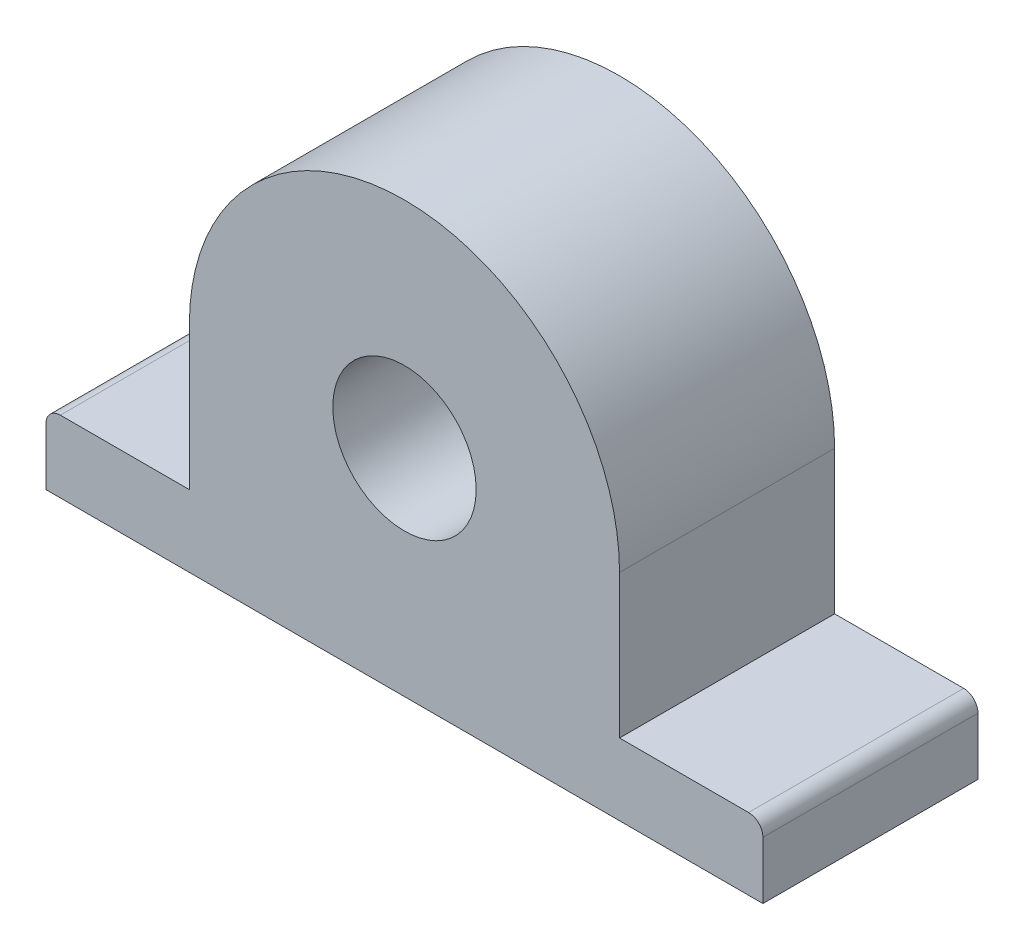
SolidWorks part; units mm, degrees
ref_plane "前视基准面" through (0, 0, 0) normal (0, 0, 1) x (1, 0, 0)
ref_plane "上视基准面" through (0, 0, 0) normal (0, 1, 0) x (1, 0, 0)
ref_plane "右视基准面" through (0, 0, 0) normal (1, 0, 0) x (0, 0, -1)
other "Configuration Table"
sketch "草图1" plane through (0, 0, 0) normal (0, 0, 1) x (1, 0, 0)
  line L0 (15, 2.5) -> (25, 2.5)
  line L1 (-25, 2.5) -> (-15, 2.5)
  line L2 (-25, 2.5) -> (-25, -2.5)
  line L3 (-25, -2.5) -> (25, -2.5)
  line L4 (25, 2.5) -> (25, -2.5)
  line L5 (-25, 2.5) -> (25, -2.5) construction
  line L6 (-25, -2.5) -> (25, 2.5) construction
  line L8 (-15, 12.5) -> (-15, 2.5)
  line L10 (15, 12.5) -> (15, 2.5)
  line L11 (-15, 12.5) -> (15, 2.5) construction
  line L12 (-15, 2.5) -> (15, 12.5) construction
  arc A1 (15, 12.5) -> (-15, 12.5) centre (0, 12.5) ccw
  circle A2 centre (0, 12.5) radius 5
  point P0 (0, 0)
  point P6 (0, 7.5)
  dimension "D3" = 30
  dimension "D4" = 5
  dimension "D6" = 10
  dimension "D1" = 10
  dimension "D2" = 10
  dimension "D5" = 50
extrude "凸台-拉伸1" add sketch "草图1" along normal blind 15
fillet "圆角1" radius 1 2 edges at (-25, 2.5, 7.5) (25, 2.5, 7.5)
